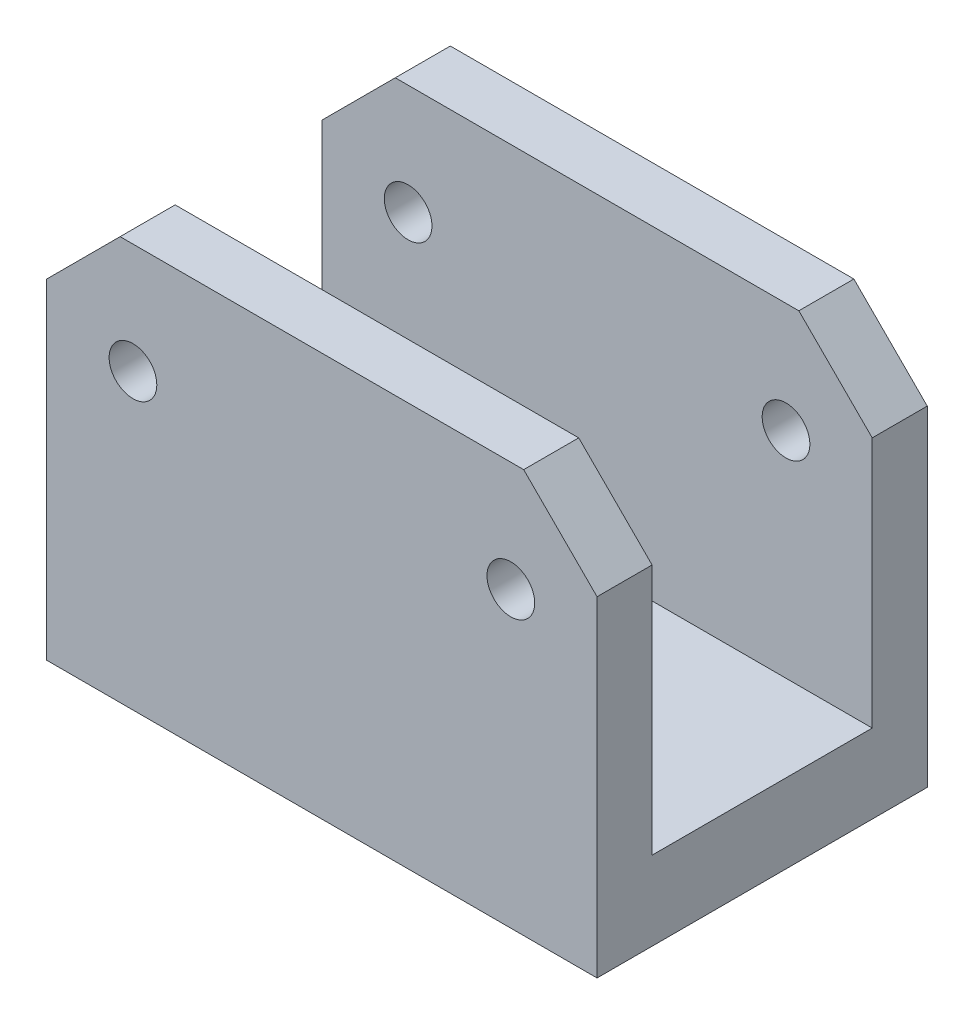
SolidWorks part; units mm, degrees
material "ABS"
ref_plane "前视基准面" through (0, 0, 0) normal (0, 0, 1) x (1, 0, 0)
ref_plane "上视基准面" through (0, 0, 0) normal (0, 1, 0) x (1, 0, 0)
ref_plane "右视基准面" through (0, 0, 0) normal (1, 0, 0) x (0, 0, -1)
other "Configuration Table"
sketch "草图2" plane through (0, 0, 0) normal (0, 0, 1) x (1, 0, 0)
  line L0 (0, 17.5458) -> (0, -16.2036) construction
  line L1 (-11, 11) -> (11, 11)
  line L2 (-15, 7) -> (-15, -11)
  line L3 (-15, -11) -> (15, -11)
  line L5 (-17.0124, 0) -> (19.7175, 0) construction
  line L7 (-15, 7) -> (-11, 11)
  line L8 (15, 7) -> (11, 11)
  line L9 (15, 7) -> (15, -11)
  circle A0 centre (-10.3, 5) radius 1.3
  circle A1 centre (10.3, 5) radius 1.3
  point P0 (0, 0)
  point P4 (0, -11)
  point P15 (0, 11)
  dimension "D4" = 2.6
  dimension "D1" = 18
  dimension "D2" = 15
  dimension "D3" = 16
  dimension "D5" = 11
  dimension "D6" = 22
  dimension "D7" = 10.3
extrude "凸台-拉伸1" add sketch "草图2" along normal mid plane 18
sketch "草图3" plane through (0, 0, 0) normal (0, 0, 1) x (1, 0, 0)
  line L0 (-15, 7) -> (-15, -11) construction
  line L1 (-15, -6.7) -> (15, -6.7)
  line L2 (-15, -6.7) -> (-15, 14.1356)
  line L3 (-15, 14.1356) -> (15, 14.1356)
  line L4 (15, -6.7) -> (15, 14.1356)
  line L5 (15, -11) -> (15, 7) construction
  line L6 (-15, -11) -> (15, -11) construction
  dimension "D1" = 4.3
extrude "切除-拉伸1" cut sketch "草图3" against normal mid plane 12
sketch "草图4" plane through (0, 0, 0) normal (0, 1, 0) x (1, 0, 0)
  circle A0 centre (0, 0) radius 1.25
  dimension "D1" = 2.5
extrude "切除-拉伸2" cut sketch "草图4" against normal up to next
